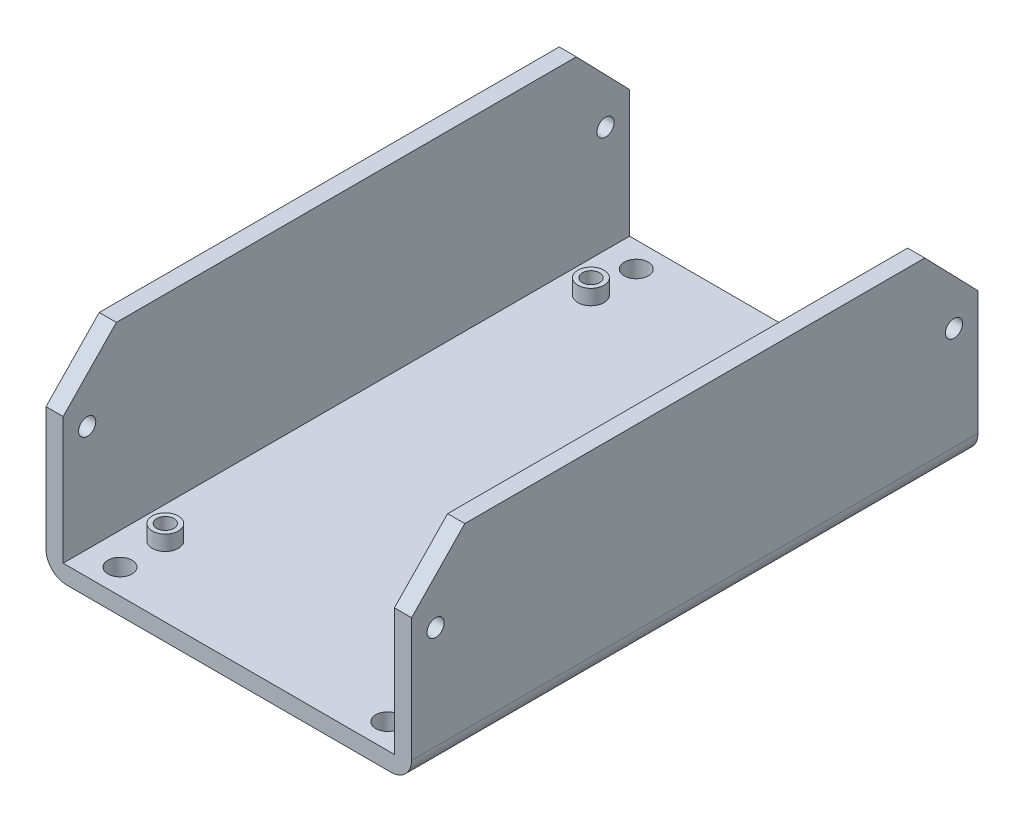
SolidWorks part; units mm, degrees
ref_plane "Спереди" through (0, 0, 0) normal (0, 0, 1) x (1, 0, 0)
ref_plane "Сверху" through (0, 0, 0) normal (0, 1, 0) x (1, 0, 0)
ref_plane "Справа" through (0, 0, 0) normal (1, 0, 0) x (0, 0, -1)
sketch "Эскиз1" plane through (0, 0, 0) normal (0, 0, 1) x (1, 0, 0)
  line L0 (-26.625, 29) -> (-26.625, 3)
  line L1 (-23.625, 0) -> (23.625, 0)
  line L2 (26.625, 3) -> (26.625, 29)
  line L3 (26.625, 29) -> (24.125, 29)
  line L4 (24.125, 29) -> (24.125, 2.5)
  line L5 (24.125, 2.5) -> (-24.125, 2.5)
  line L6 (-24.125, 2.5) -> (-24.125, 29)
  line L7 (-24.125, 29) -> (-26.625, 29)
  arc A0 (23.625, 0) -> (26.625, 3) centre (23.625, 3) ccw
  arc A1 (-26.625, 3) -> (-23.625, 0) centre (-23.625, 3) ccw
  point P12 (26.625, 0)
  point P15 (-26.625, 0)
  dimension "D5" = 3
  dimension "D1" = 53.25
  dimension "D2" = 2.5
  dimension "D3" = 2.5
  dimension "D4" = 29
extrude "Бобышка-Вытянуть1" add sketch "Эскиз1" along normal mid plane 82.5
sketch "Эскиз3" plane through (0, 0, 0) normal (1, 0, 0) x (0, 0, -1)
  line L0 (41.25, 3) -> (41.25, 29) construction
  line L1 (-41.25, 3) -> (-41.25, 29) construction
  line L2 (-41.25, 29) -> (41.25, 29) construction
  line L3 (41.25, 21) -> (41.25, 29)
  line L4 (-41.25, 21) -> (-41.25, 29)
  line L5 (-41.25, 29) -> (-33.5, 29)
  line L6 (-41.25, 21) -> (-33.5, 29)
  line L7 (33.5, 29) -> (41.25, 21)
  line L8 (33.5, 29) -> (41.25, 29)
  line L9 (-33.5, 29) -> (33.5, 29) construction
  line L10 (-41.25, 0) -> (41.25, 0) construction
  point P8 (0, 29)
  dimension "D1" = 67
  dimension "D2" = 21
extrude "Вырез-Вытянуть1" cut sketch "Эскиз3" against normal through all and the other way through all
sketch "Эскиз4" plane through (0, 0, 0) normal (0, -1, 0) x (1, 0, 0)
  line L1 (19.5, -37.6) -> (-19.5, -37.6) construction
  line L2 (19.5, -37.6) -> (19.5, 37.6) construction
  line L3 (19.5, 37.6) -> (-19.5, 37.6) construction
  line L4 (-19.5, -37.6) -> (-19.5, 37.6) construction
  line L5 (19.5, -37.6) -> (-19.5, 37.6) construction
  line L6 (19.5, 37.6) -> (-19.5, -37.6) construction
  circle A0 centre (-19.5, -37.6) radius 1.75
  circle A1 centre (-19.5, 37.6) radius 1.75
  circle A2 centre (19.5, 37.6) radius 1.75
  circle A3 centre (19.5, -37.6) radius 1.75
  point P0 (0, 0)
  dimension "D1" = 3.5
  dimension "D2" = 75.2
  dimension "D3" = 39
extrude "Вырез-Вытянуть2" cut sketch "Эскиз4" against normal blind 10
hole_wizard "Отверстие обработанное метчиком M31" positions "Эскиз5" profile "Эскиз6" tap size "M3" standard "DIN"
sketch "Эскиз5" plane through (26.625, 0, 0) normal (1, 0, 0) x (0, 0, -1)
  line L0 (37.75, 18) -> (-37.75, 18) construction
  line L2 (-33.5, 29) -> (33.5, 29) construction
  point P0 (37.75, 18)
  point P2 (-37.75, 18)
  point P9 (0, 18)
  dimension "D1" = 75.5
  dimension "D2" = 11
cosmetic thread "Отверстие резьбы1"
cosmetic thread "Отверстие резьбы2"
sketch "Эскиз6" plane through (26.625, 18, -37.75) normal (0, 1, 0) x (0, 0, -1)
  line L0 (0, 0) -> (0, 3.2501)
  line L1 (0, 3.2501) -> (1.25, 2.499)
  line L2 (1.25, 2.499) -> (1.25, 0)
  line L5 (1.25, 0) -> (0, 0)
  line L10 (0, 3.2501) -> (-1.25, 2.499) construction
  line L11 (0, -6.35) -> (0, 107.95) construction
  dimension "Диаметр сверла" = 2.5
  dimension "Глубина сверла" = 2.499
  dimension "Угол заточки сверла" = 118
hole_wizard "Отверстие обработанное метчиком M32" positions "Эскиз8" profile "Эскиз9" tap size "M3" standard "DIN"
sketch "Эскиз8" plane through (-26.625, 0, 0) normal (-1, 0, 0) x (0, 0, 1)
  point P0 (-37.75, 18)
  point P3 (37.75, 18)
sketch "Эскиз9" plane through (-26.625, 18, -37.75) normal (0, 1, 0) x (0, 0, 1)
  line L0 (0, 0) -> (0, 3.2501)
  line L1 (0, 3.2501) -> (1.25, 2.499)
  line L2 (1.25, 2.499) -> (1.25, 0)
  line L5 (1.25, 0) -> (0, 0)
  line L10 (0, 3.2501) -> (-1.25, 2.499) construction
  line L11 (0, -6.35) -> (0, 107.95) construction
  dimension "Диаметр сверла" = 2.5
  dimension "Глубина сверла" = 2.499
  dimension "Угол заточки сверла" = 118
cosmetic thread "Отверстие резьбы3"
cosmetic thread "Отверстие резьбы4"
sketch "Эскиз10" plane through (0, 2.5, 0) normal (0, 1, 0) x (1, 0, 0)
  line L1 (-19.5, 31) -> (19.5, 31) construction
  line L2 (-19.5, 31) -> (-19.5, -31) construction
  line L3 (-19.5, -31) -> (19.5, -31) construction
  line L4 (19.5, 31) -> (19.5, -31) construction
  line L5 (-19.5, 31) -> (19.5, -31) construction
  line L6 (-19.5, -31) -> (19.5, 31) construction
  circle A0 centre (19.5, 31) radius 1.9
  circle A1 centre (19.5, -31) radius 1.9
  circle A2 centre (-19.5, -31) radius 1.9
  circle A3 centre (-19.5, 31) radius 1.9
  point P0 (0, 0)
  dimension "D1" = 3.8
  dimension "D2" = 62
  dimension "D3" = 39
extrude "Бобышка-Вытянуть2" add sketch "Эскиз10" along normal blind 2.2
hole_wizard "Отверстие обработанное метчиком M33" positions "Эскиз11" profile "Эскиз12" tap size "M3" standard "DIN" end condition through all
sketch "Эскиз11" plane through (0, 4.7, 0) normal (0, 1, 0) x (1, 0, 0)
  point P0 (19.5, 31)
  point P3 (-19.5, 31)
  point P6 (19.5, -31)
  point P9 (-19.5, -31)
sketch "Эскиз12" plane through (19.5, 4.7, -31) normal (1, 0, 0) x (0, 0, 1)
  line L0 (0, 0) -> (0, 4.7)
  line L1 (0, 4.7) -> (1.25, 4.7)
  line L2 (1.25, 4.7) -> (1.25, 0)
  line L5 (1.25, 0) -> (0, 0)
  line L11 (0, -6.35) -> (0, 107.95) construction
  dimension "Диаметр проходного сверла" = 2.5
  dimension "Глубина проходного сверла" = 4.7
cosmetic thread "Отверстие резьбы5"
cosmetic thread "Отверстие резьбы6"
cosmetic thread "Отверстие резьбы7"
cosmetic thread "Отверстие резьбы8"
